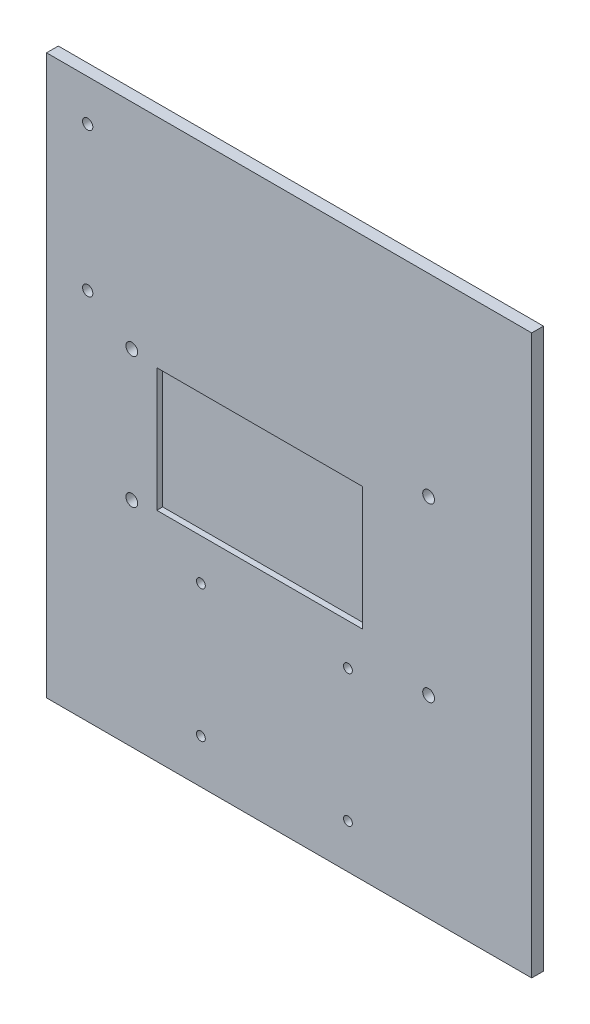
SolidWorks part; units mm, degrees
ref_plane "Plan de face" through (0, 0, 0) normal (0, 0, 1) x (1, 0, 0)
ref_plane "Plan de dessus" through (0, 0, 0) normal (0, 1, 0) x (1, 0, 0)
ref_plane "Plan de droite" through (0, 0, 0) normal (1, 0, 0) x (0, 0, -1)
sketch "Esquisse1" plane through (0, 0, 0) normal (0, 0, 1) x (1, 0, 0)
  line L1 (0, 0) -> (165, 0)
  line L2 (0, 0) -> (0, 190)
  line L3 (0, 190) -> (165, 190)
  line L4 (165, 0) -> (165, 190)
  dimension "D1" = 165
  dimension "D2" = 190
extrude "Boss.-Extru.1" add sketch "Esquisse1" along normal blind 4
sketch "Esquisse2" plane through (0, 0, 0) normal (0, 0, -1) x (-1, 0, 0)
  line L0 (-165, 190) -> (0, 190) construction
  line L1 (0, 0) -> (-165, 0) construction
  line L2 (-165, 0) -> (-165, 190) construction
  line L3 (-129.9343, 124.25) -> (-129.9343, 28.7927) construction
  line L4 (0, 190) -> (0, 0) construction
  circle A0 centre (-129.9343, 124.25) radius 2
  circle A1 centre (-29, 117.25) radius 2
  circle A2 centre (-29, 72.75) radius 2
  circle A3 centre (-129.9343, 65.75) radius 2
  dimension "D1" = 4
  dimension "D2" = 4
  dimension "D3" = 4
  dimension "D4" = 4
  dimension "D9" = 29
  dimension "D5" = 65.75
  dimension "D6" = 65.75
  dimension "D7" = 35.0657
  dimension "D8" = 29
  dimension "D10" = 72.75
  dimension "D11" = 72.75
extrude "Enlèv. mat.-Extru.1" cut sketch "Esquisse2" against normal blind 10
sketch "Esquisse3" plane through (0, 0, 4) normal (0, 0, 1) x (1, 0, 0)
  line L0 (10, 123) -> (10, 180) construction
  line L1 (10, 123) -> (124, 123) construction
  line L2 (10, 180) -> (124, 180) construction
  line L3 (124, 180) -> (124, 123) construction
  line L4 (0, 190) -> (0, 0) construction
  line L5 (165, 190) -> (0, 190) construction
  circle A0 centre (14, 176) radius 1.75
  circle A1 centre (14, 127) radius 1.75
  dimension "D2" = 3.5
  dimension "D3" = 3.5
  dimension "D1" = 49
  dimension "D4" = 57
  dimension "D5" = 114
  dimension "D6" = 4
  dimension "D7" = 4
  dimension "D8" = 4
  dimension "D9" = 10
  dimension "D10" = 10
extrude "Enlèv. mat.-Extru.2" cut sketch "Esquisse3" against normal blind 10
sketch "Esquisse4" plane through (0, 0, 4) normal (0, 0, 1) x (1, 0, 0)
  line L0 (0, 0) -> (165, 0) construction
  line L1 (47.5, 10) -> (107.5, 10) construction
  line L2 (47.5, 10) -> (47.5, 65) construction
  line L3 (47.5, 65) -> (107.5, 65) construction
  line L4 (107.5, 10) -> (107.5, 65) construction
  line L5 (0, 190) -> (0, 0) construction
  circle A0 centre (52.5, 15) radius 1.5
  circle A1 centre (52.5, 60) radius 1.5
  circle A2 centre (102.5, 60) radius 1.5
  circle A3 centre (102.5, 15) radius 1.5
  dimension "D5" = 3
  dimension "D6" = 3
  dimension "D7" = 3
  dimension "D8" = 3
  dimension "D9" = 5
  dimension "D14" = 5
  dimension "D1" = 60
  dimension "D2" = 55
  dimension "D3" = 10
  dimension "D4" = 47.5
  dimension "D10" = 5
  dimension "D11" = 5
  dimension "D12" = 5
  dimension "D13" = 5
  dimension "D15" = 5
  dimension "D16" = 5
extrude "Enlèv. mat.-Extru.3" cut sketch "Esquisse4" against normal blind 10
sketch "Esquisse5" plane through (0, 0, 4) normal (0, 0, 1) x (1, 0, 0)
  line L0 (0, 190) -> (0, 0) construction
  line L1 (37.5, 74) -> (107.5, 74)
  line L2 (37.5, 74) -> (37.5, 116)
  line L3 (37.5, 116) -> (107.5, 116)
  line L4 (107.5, 74) -> (107.5, 116)
  line L5 (165, 190) -> (0, 190) construction
  dimension "D1" = 42
  dimension "D2" = 70
  dimension "D3" = 37.5
  dimension "D4" = 74
extrude "Enlèv. mat.-Extru.4" cut sketch "Esquisse5" against normal blind 2
